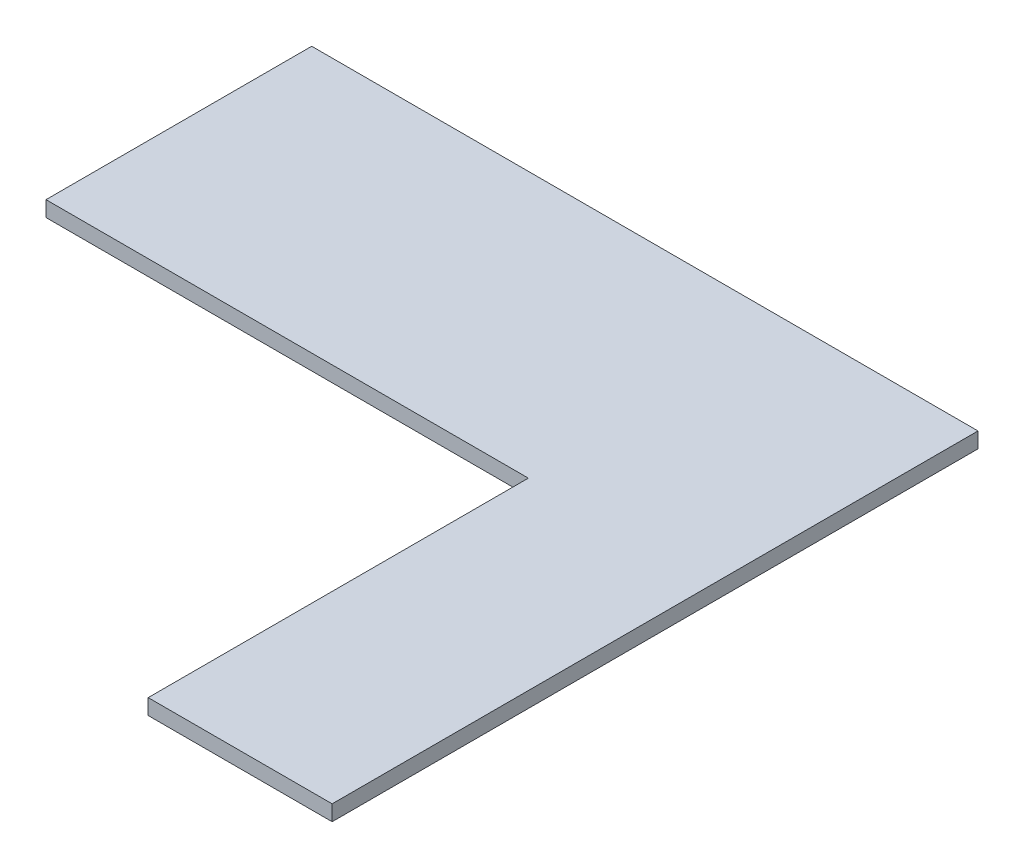
SolidWorks part; units mm, degrees
ref_plane "Спереди" through (0, 0, 0) normal (0, 0, 1) x (1, 0, 0)
ref_plane "Сверху" through (0, 0, 0) normal (0, 1, 0) x (1, 0, 0)
ref_plane "Справа" through (0, 0, 0) normal (1, 0, 0) x (0, 0, -1)
sketch "Эскиз1" plane through (0, 0, 0) normal (0, 1, 0) x (1, 0, 0)
  line L0 (0, 0) -> (0, 650)
  line L1 (0, 650) -> (1630, 650)
  line L2 (1630, 650) -> (1630, -930)
  line L3 (1630, -930) -> (1180, -930)
  line L4 (1180, -930) -> (1180, 0)
  line L5 (1180, 0) -> (0, 0)
extrude "Бобышка-Вытянуть1" add sketch "Эскиз1" along normal blind 38
